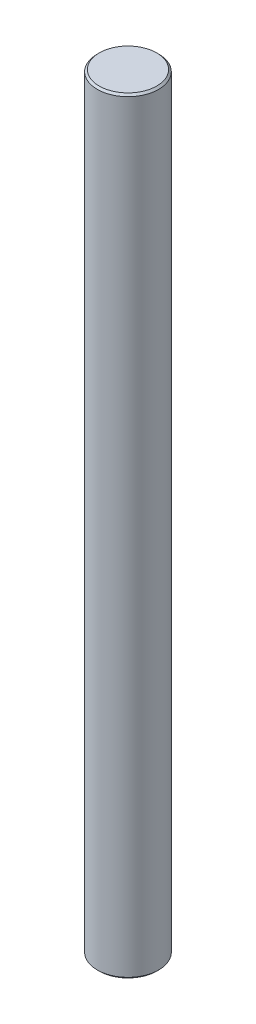
SolidWorks part; units mm, degrees
ref_plane "Front" through (0, 0, 0) normal (0, 0, 1) x (1, 0, 0)
ref_plane "Top" through (0, 0, 0) normal (0, 1, 0) x (1, 0, 0)
ref_plane "Right" through (0, 0, 0) normal (1, 0, 0) x (0, 0, -1)
sketch "Sketch2" plane through (0, 0, 0) normal (0, 1, 0) x (1, 0, 0)
  circle A0 centre (0, 0) radius 4
  dimension "D1" = 8
extrude "Boss-Extrude1" add sketch "Sketch2" along normal blind 100
chamfer "Chamfer1" distance 0.25 angle 45 2 edges at (0, 100, 4) (0, 0, 4)
